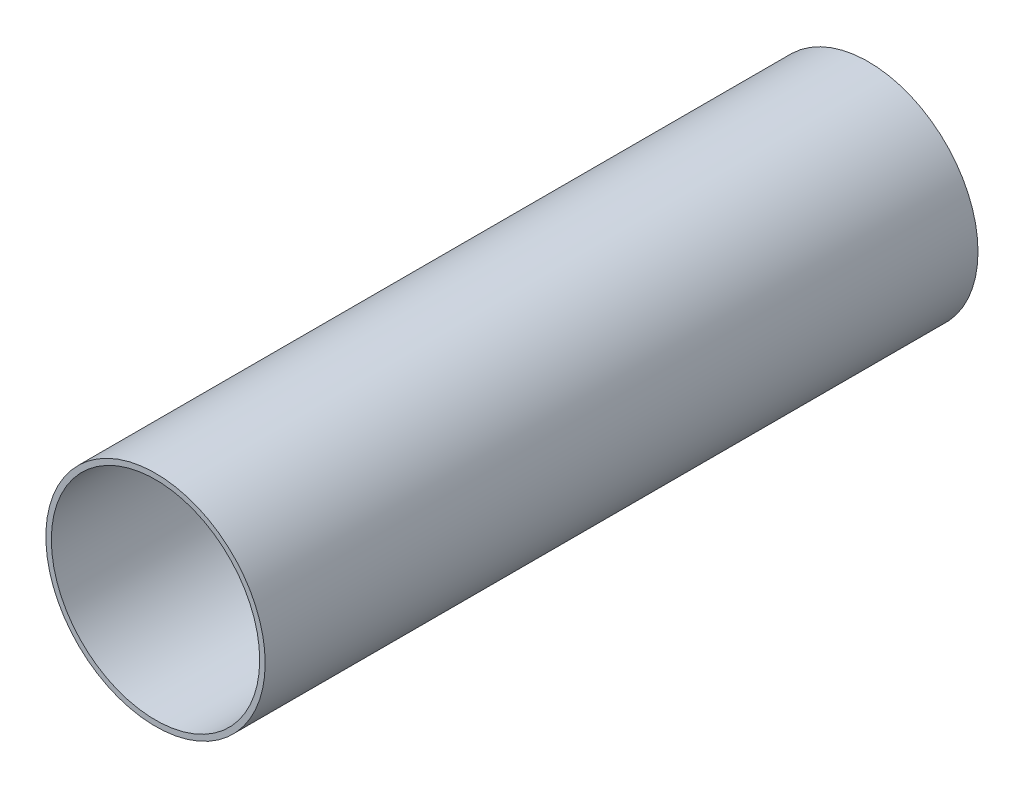
SolidWorks part; units mm, degrees
material "ABS PC"
ref_plane "Front Plane" through (0, 0, 0) normal (0, 0, 1) x (1, 0, 0)
ref_plane "Top Plane" through (0, 0, 0) normal (0, 1, 0) x (1, 0, 0)
ref_plane "Right Plane" through (0, 0, 0) normal (1, 0, 0) x (0, 0, -1)
sketch "Sketch1" plane through (0, 0, 0) normal (0, 0, 1) x (1, 0, 0)
  circle A0 centre (0, 0) radius 20
  circle A1 centre (0, 0) radius 19
  dimension "D1" = 40
  dimension "D2" = 38
extrude "Boss-Extrude1" add sketch "Sketch1" along normal mid plane 130
